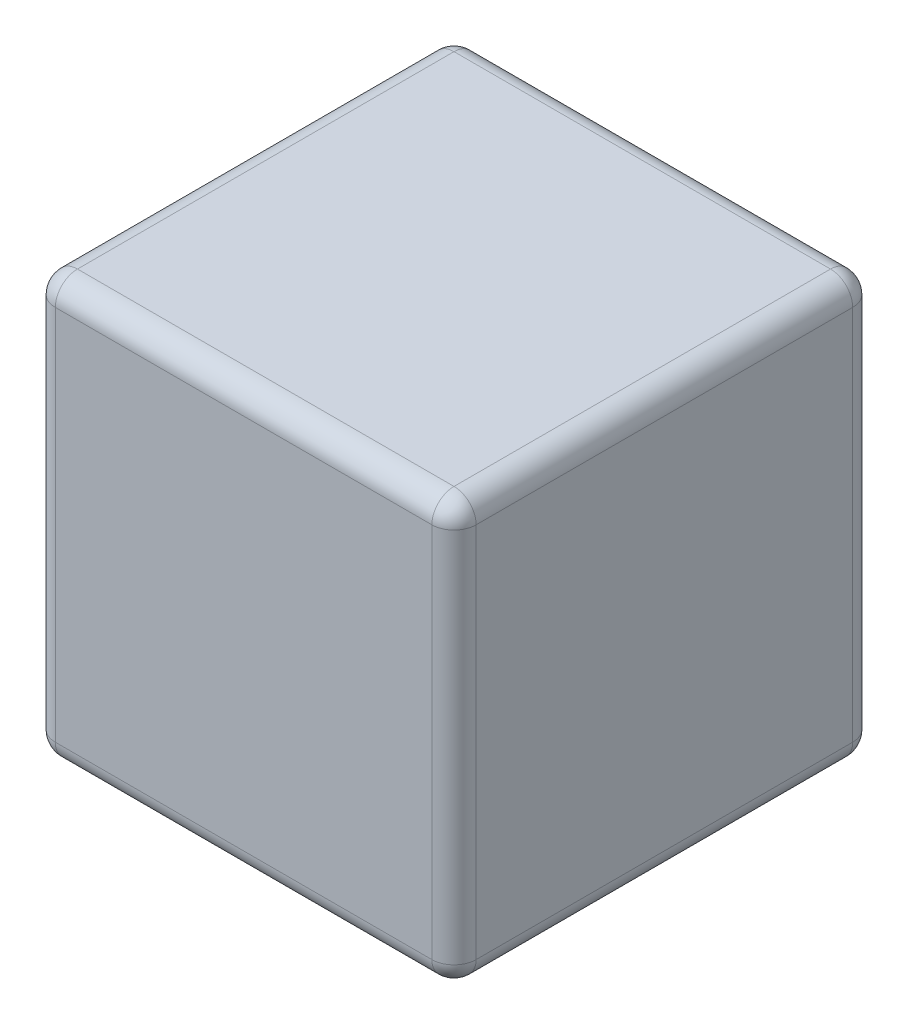
SolidWorks part; units mm, degrees
ref_plane "Front Plane" through (0, 0, 0) normal (0, 0, 1) x (1, 0, 0)
ref_plane "Top Plane" through (0, 0, 0) normal (0, 1, 0) x (1, 0, 0)
ref_plane "Right Plane" through (0, 0, 0) normal (1, 0, 0) x (0, 0, -1)
sketch "Sketch1" plane through (0, 0, 0) normal (0, 0, 1) x (1, 0, 0)
  line L1 (955.9192, -129.9308) -> (1197.2192, -129.9308)
  line L2 (955.9192, -129.9308) -> (955.9192, 111.3692)
  line L3 (955.9192, 111.3692) -> (1197.2192, 111.3692)
  line L4 (1197.2192, -129.9308) -> (1197.2192, 111.3692)
  point P4 (0, 0)
  dimension "D1" = 241.3
extrude "Boss-Extrude1" add sketch "Sketch1" along normal blind 241.3
fillet "Fillet1" radius 12.7 12 edges at (1076.5692, -129.9308, 0) (1076.5692, -129.9308, 241.3) (1076.5692, 111.3692, 0) (1076.5692, 111.3692, 241.3) (955.9192, 111.3692, 120.65) (1197.2192, -129.9308, 120.65) (955.9192, -129.9308, 120.65) (1197.2192, 111.3692, 120.65) (955.9192, -9.2808, 0) (955.9192, -9.2808, 241.3) (1197.2192, -9.2808, 0) (1197.2192, -9.2808, 241.3)
